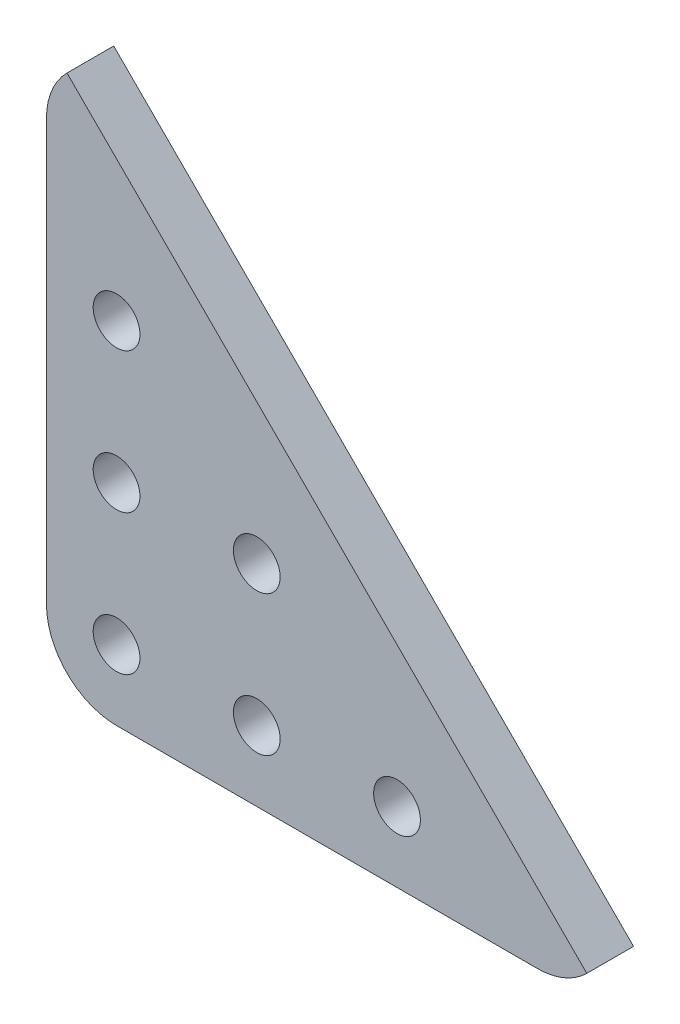
SolidWorks part; units mm, degrees
ref_plane "Alzado" through (0, 0, 0) normal (0, 0, 1) x (1, 0, 0)
ref_plane "Planta" through (0, 0, 0) normal (0, 1, 0) x (1, 0, 0)
ref_plane "Vista lateral" through (0, 0, 0) normal (1, 0, 0) x (0, 0, -1)
sketch "Model" plane through (0, 0, 0) normal (0, 0, 1) x (1, 0, 0)
  line L0 (-105.9434, 101.0565) -> (-105.9434, 74.0565)
  line L1 (-101.4434, 69.5565) -> (-74.4434, 69.5565)
  line L2 (-104.6254, 104.2385) -> (-71.2614, 70.8746)
  circle A0 centre (-101.4434, 92.0565) radius 1.5
  circle A1 centre (-101.4434, 83.0565) radius 1.5
  circle A2 centre (-92.4434, 83.0565) radius 1.5
  circle A3 centre (-101.4434, 74.0565) radius 1.5
  circle A4 centre (-92.4434, 74.0565) radius 1.5
  circle A5 centre (-83.4434, 74.0565) radius 1.5
  arc A6 (-104.6254, 104.2385) -> (-105.9434, 101.0565) centre (-101.4434, 101.0565) ccw
  arc A7 (-105.9434, 74.0565) -> (-101.4434, 69.5565) centre (-101.4434, 74.0565) ccw
  arc A8 (-74.4434, 69.5565) -> (-71.2614, 70.8746) centre (-74.4434, 74.0565) ccw
extrude "Saliente-Extruir1" add sketch "Model" along normal blind 3
